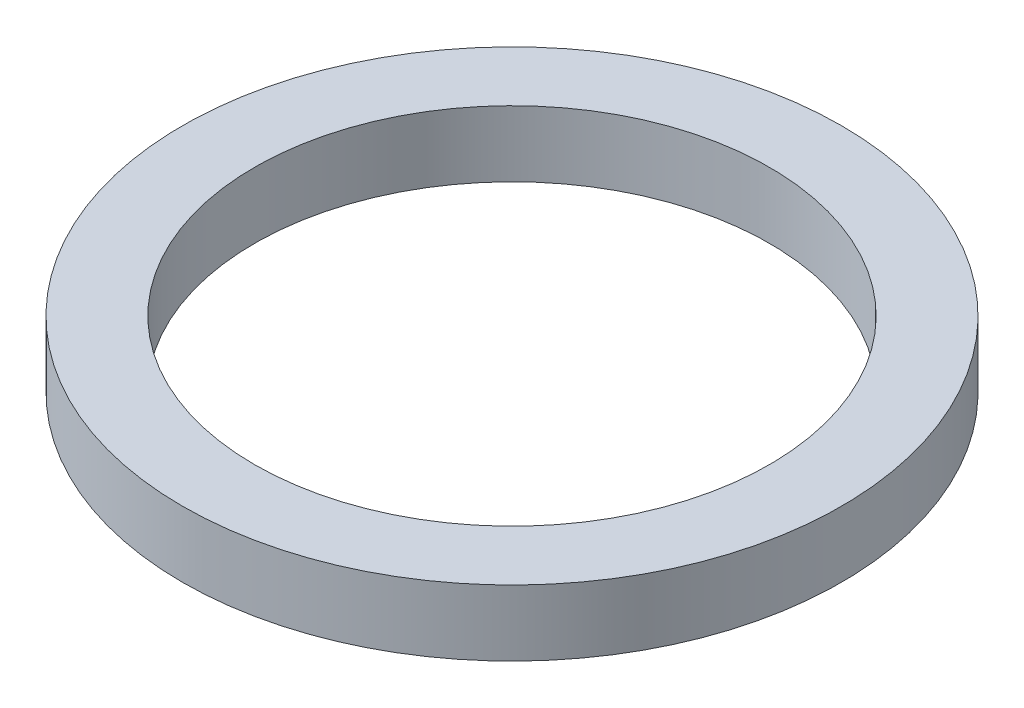
SolidWorks part; units mm, degrees
ref_plane "Front Plane" through (0, 0, 0) normal (0, 0, 1) x (1, 0, 0)
ref_plane "Top Plane" through (0, 0, 0) normal (0, 1, 0) x (1, 0, 0)
ref_plane "Right Plane" through (0, 0, 0) normal (1, 0, 0) x (0, 0, -1)
sketch "Sketch1" plane through (0, 0, 0) normal (0, 1, 0) x (1, 0, 0)
  circle A2 centre (0, 0) radius 25
  circle A3 centre (0, 0) radius 19.535
  dimension "D1" = 50
  dimension "D2" = 50
extrude "Boss-Extrude1" add sketch "Sketch1" along normal blind 5
